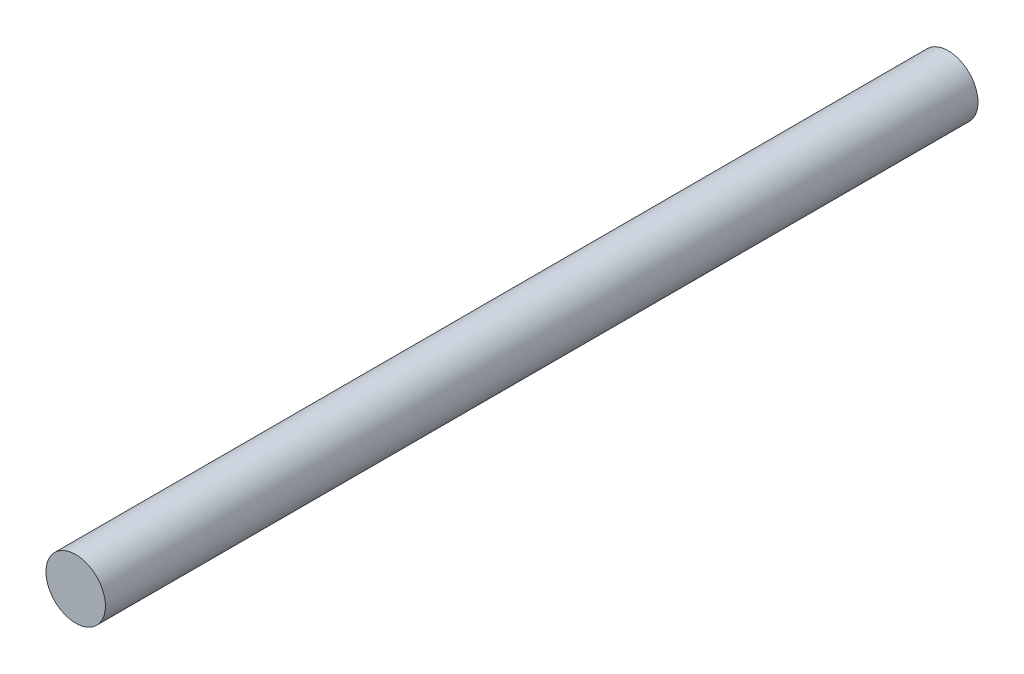
SolidWorks part; units mm, degrees
material "AISI 1010 Steel, hot rolled bar"
ref_plane "Front Plane" through (0, 0, 0) normal (0, 0, 1) x (1, 0, 0)
ref_plane "Top Plane" through (0, 0, 0) normal (0, 1, 0) x (1, 0, 0)
ref_plane "Right Plane" through (0, 0, 0) normal (1, 0, 0) x (0, 0, -1)
sketch "Sketch1" plane through (0, 0, 0) normal (0, 0, 1) x (1, 0, 0)
  circle A0 centre (0, 0) radius 4.7625
  dimension "D1" = 9.525
extrude "Boss-Extrude1" add sketch "Sketch1" along normal blind 139.7
ref_plane "Plane1" through (0, 0, 69.85) normal (0, 0, 1) x (1, 0, 0)
